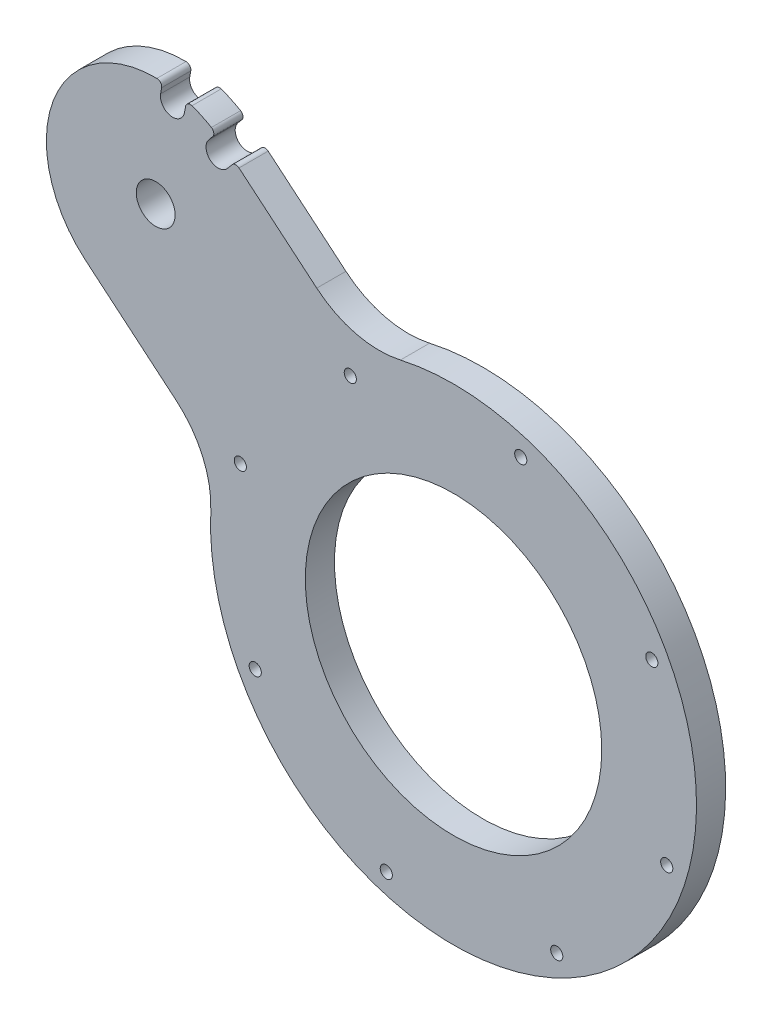
SolidWorks part; units mm, degrees
ref_plane "前视基准面" through (0, 0, 0) normal (0, 0, 1) x (1, 0, 0)
ref_plane "上视基准面" through (0, 0, 0) normal (0, 1, 0) x (1, 0, 0)
ref_plane "右视基准面" through (0, 0, 0) normal (1, 0, 0) x (0, 0, -1)
other "Configuration Table"
sketch "草图1" plane through (0, 0, 0) normal (0, 0, 1) x (1, 0, 0)
  line L0 (0, 0) -> (0, -64.4108) construction
  line L2 (-28.1458, 52.9888) -> (-44.1397, 66.4093)
  line L13 (0, 0) -> (-98.0331, 82.2595) construction
  line L14 (-61.2836, 51.423) -> (-33.6298, 84.3795) construction
  line L15 (-57.0713, 18.5168) -> (-75.7463, 34.187)
  line L16 (-48.4278, 66.7439) -> (-40.9351, 75.6734) construction
  line L17 (-50.3429, 68.3509) -> (-49.5631, 69.2802)
  line L18 (-46.5127, 65.1369) -> (-45.5485, 66.286)
  line L19 (-61.2836, 51.423) -> (-57.11, 75.0925) construction
  line L20 (-57.8106, 71.1192) -> (-56.7348, 77.22) construction
  line L21 (-60.2726, 71.5533) -> (-60.0619, 72.7481)
  line L22 (-55.3486, 70.685) -> (-55.1379, 71.8798)
  arc A12 (-49.9479, 2.2828) -> (-10.9215, 48.7926) centre (0, 0) ccw
  arc A16 (-49.9479, 2.2828) -> (-57.0713, 18.5168) centre (-69.927, 3.1959) ccw
  arc A17 (-10.9215, 48.7926) -> (-28.1458, 52.9888) centre (-15.2901, 68.3097) cw
  circle A18 centre (-61.2836, 51.423) radius 4
  arc A20 (-50.3429, 68.3509) -> (-46.5127, 65.1369) centre (-48.4278, 66.7439) ccw
  arc A22 (-49.8196, 70.7835) -> (-53.8214, 72.6496) centre (-61.2836, 51.423) ccw
  arc A24 (-49.5631, 69.2802) -> (-49.8196, 70.7835) centre (-50.3291, 69.923) ccw
  arc A25 (-60.2726, 71.5533) -> (-55.3486, 70.685) centre (-57.8106, 71.1192) ccw
  arc A28 (-60.0619, 72.7481) -> (-61.0357, 73.9216) centre (-61.0467, 72.9217) ccw
  arc A29 (-55.1379, 71.8798) -> (-53.8214, 72.6496) centre (-54.1531, 71.7062) cw
  arc A30 (-45.5485, 66.286) -> (-44.1397, 66.4093) centre (-44.7825, 65.6432) cw
  arc A31 (-61.0357, 73.9216) -> (-75.7463, 34.187) centre (-61.2836, 51.423) ccw
  point P15 (-61.2836, 77.8828)
  point P26 (-48.8255, 70.1593)
  point P29 (-73.0936, 71.8786)
  point P36 (-59.8627, 73.8781)
  dimension "D13" = 30
  dimension "D14" = 20
  dimension "D15" = 2.5
  dimension "D17" = 5
  dimension "D19" = 2.5
  dimension "D20" = 100
  dimension "D21" = 2.5
  dimension "D22" = 32.9565
  dimension "D3" = 2.5
  dimension "D7" = 20
  dimension "D8" = 20
  dimension "D9" = 8
  dimension "D10" = 80
  dimension "D11" = 20
  dimension "D12" = 1
  dimension "D16" = 1
  dimension "D24" = 22.5
  dimension "D25" = 22.5
  dimension "D26" = 1
  dimension "D27" = 1
  dimension "D28" = 1
  dimension "D4" = 50
  dimension "D5" = 45
  dimension "D6" = 22.5
  dimension "D18" = 5
  dimension "D23" = 60
extrude "凸台-拉伸2" add sketch "草图1" along normal blind 1 and the other way blind 5
sketch "草图2" plane through (0, 0, 1) normal (0, 0, 1) x (1, 0, 0)
  line L0 (0, 0) -> (-61.2836, 51.423) construction
  line L1 (0, 0) -> (-21.2404, 40.8025) construction
  line L2 (0, 0) -> (-43.871, 13.8325) construction
  line L3 (0, 0) -> (-40.8025, -21.2404) construction
  line L4 (0, 0) -> (-13.8325, -43.871) construction
  line L5 (0, 0) -> (21.2404, -40.8025) construction
  line L6 (0, 0) -> (43.871, -13.8325) construction
  line L7 (0, 0) -> (40.8025, 21.2404) construction
  line L8 (0, 0) -> (13.8325, 43.871) construction
  circle A0 centre (0, 0) radius 46 construction
  circle A1 centre (-21.2404, 40.8025) radius 1.25
  circle A2 centre (13.8325, 43.871) radius 1.25
  circle A3 centre (40.8025, 21.2404) radius 1.25
  circle A4 centre (43.871, -13.8325) radius 1.25
  circle A5 centre (21.2404, -40.8025) radius 1.25
  circle A6 centre (-13.8325, -43.871) radius 1.25
  circle A7 centre (-40.8025, -21.2404) radius 1.25
  circle A8 centre (-43.871, 13.8325) radius 1.25
  circle A9 centre (0, 0) radius 30.5
  dimension "D1" = 92
  dimension "D11" = 2.5
  dimension "D12" = 2.5
  dimension "D13" = 2.5
  dimension "D14" = 2.5
  dimension "D15" = 2.5
  dimension "D16" = 2.5
  dimension "D17" = 2.5
  dimension "D18" = 2.5
  dimension "D19" = 61
  dimension "D2" = 22.5
  dimension "D3" = 45
  dimension "D4" = 45
  dimension "D5" = 45
  dimension "D6" = 45
  dimension "D7" = 45
  dimension "D8" = 45
  dimension "D9" = 45
  dimension "D10" = 45
extrude "切除-拉伸1" cut sketch "草图2" against normal blind 10
sketch "草图3" plane through (0, 0, -5) normal (0, 0, -1) x (-1, 0, 0)
  circle A0 centre (-13.8325, 43.871) radius 2.5
  circle A1 centre (21.2404, 40.8025) radius 2.5
  circle A2 centre (43.871, 13.8325) radius 2.5
  circle A3 centre (40.8025, -21.2404) radius 2.5
  circle A4 centre (13.8325, -43.871) radius 2.5
  circle A5 centre (-21.2404, -40.8025) radius 2.5
  circle A6 centre (-43.871, -13.8325) radius 2.5
  circle A7 centre (-40.8025, 21.2404) radius 2.5
  dimension "D1" = 5
  dimension "D2" = 5
  dimension "D3" = 5
  dimension "D4" = 5
  dimension "D5" = 5
  dimension "D6" = 5
  dimension "D7" = 5
  dimension "D8" = 5
extrude "切除-拉伸2" cut sketch "草图3" against normal blind 1.5
